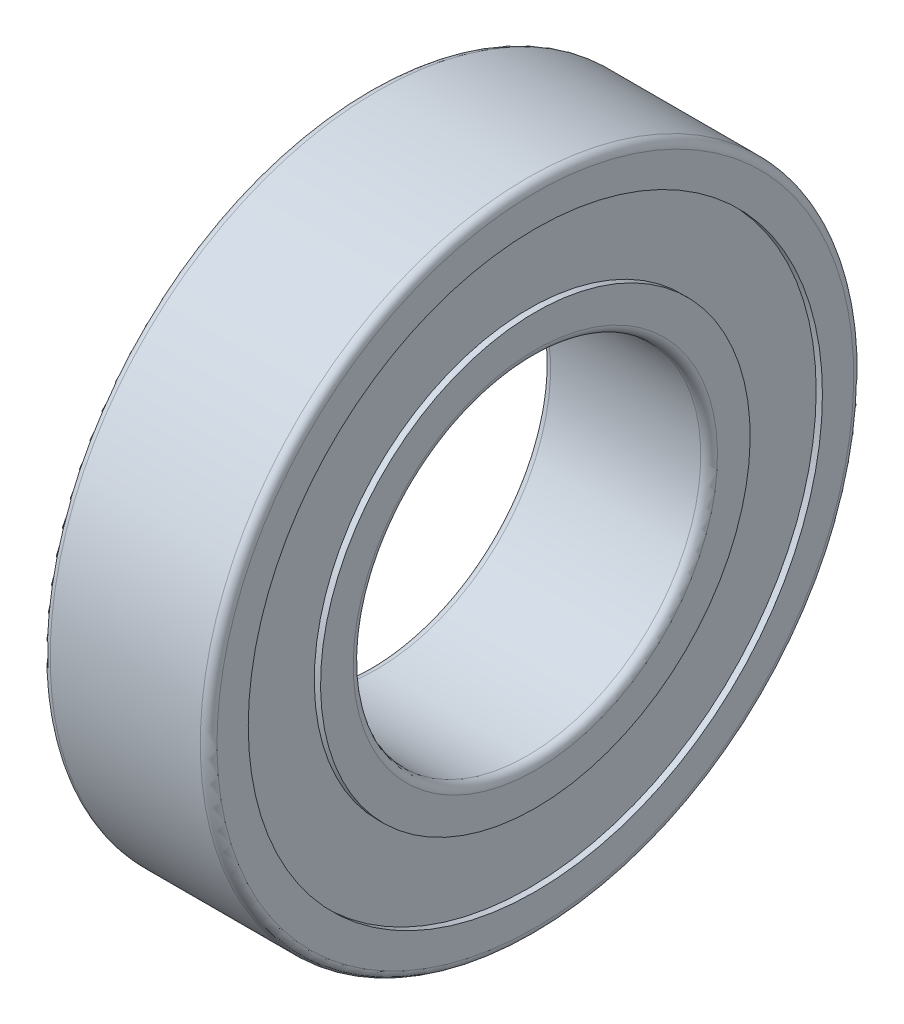
SolidWorks part; units mm, degrees
ref_plane "Front Plane" through (0, 0, 0) normal (0, 0, 1) x (1, 0, 0)
ref_plane "Top Plane" through (0, 0, 0) normal (0, 1, 0) x (1, 0, 0)
ref_plane "Right Plane" through (0, 0, 0) normal (1, 0, 0) x (0, 0, -1)
sketch "Sketch1" plane through (0, 0, 0) normal (0, 0, 1) x (1, 0, 0)
  line L0 (0, 0) -> (12, 0) construction
  line L1 (0, 12.5) -> (0, 15.45)
  line L2 (0, 15.45) -> (0.45, 15.45)
  line L3 (0.45, 15.45) -> (0.45, 20.65)
  line L4 (0.45, 20.65) -> (0, 20.65)
  line L5 (0, 20.65) -> (0, 23.5)
  line L6 (0, 23.5) -> (12, 23.5)
  line L7 (12, 23.5) -> (12, 20.65)
  line L8 (12, 20.65) -> (11.55, 20.65)
  line L9 (11.55, 20.65) -> (11.55, 15.45)
  line L10 (11.55, 15.45) -> (12, 15.45)
  line L11 (12, 15.45) -> (12, 12.5)
  line L12 (12, 12.5) -> (0, 12.5)
  dimension "D_s" = 25
  dimension "D" = 47
  dimension "B" = 12
  dimension "MSM_3" = 30.9
  dimension "MSM_4" = 41.3
  dimension "MSM_5" = 11.1
revolve "Revolve1" add sketch "Sketch1" angle 360 about L0
fillet "Fillet1" radius 0.6 4 edges at (0, -12.5, 0) (12, -12.5, 0) (0, -23.5, 0) (12, -23.5, 0)
